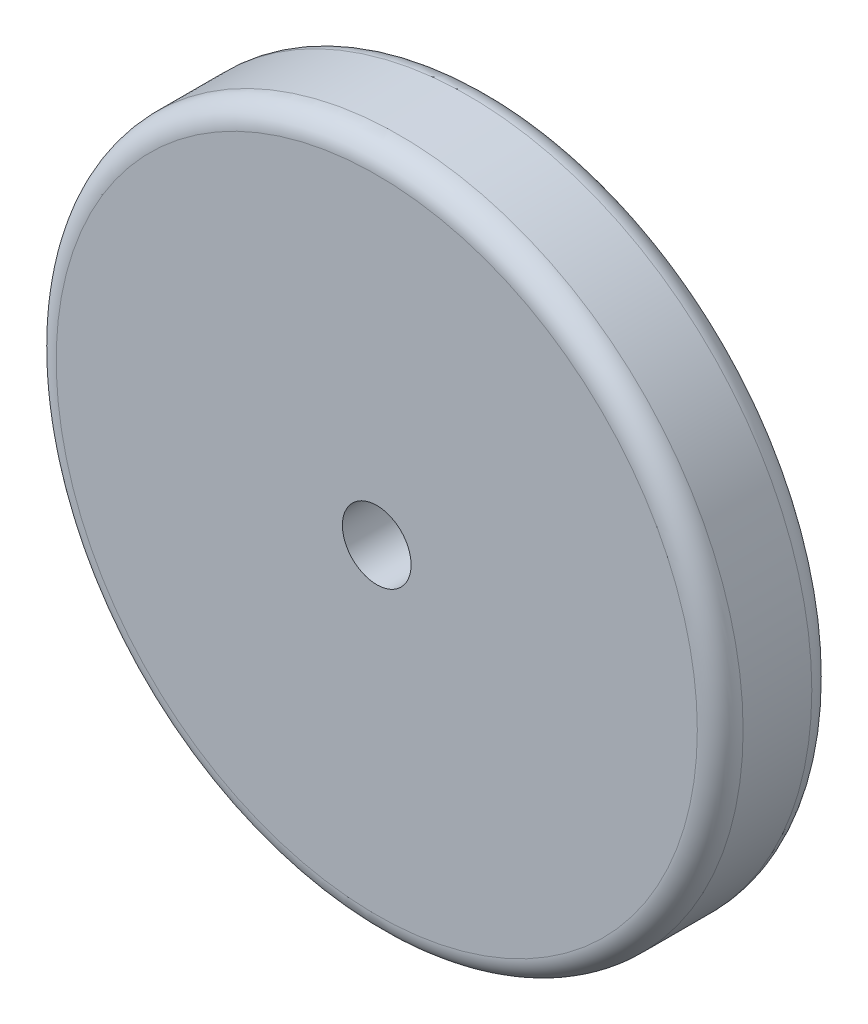
SolidWorks part; units mm, degrees
ref_plane "Alzado" through (0, 0, 0) normal (0, 0, 1) x (1, 0, 0)
ref_plane "Planta" through (0, 0, 0) normal (0, 1, 0) x (1, 0, 0)
ref_plane "Vista lateral" through (0, 0, 0) normal (1, 0, 0) x (0, 0, -1)
sketch "Croquis1" plane through (0, 0, 0) normal (0, 0, 1) x (1, 0, 0)
  circle A0 centre (0, 0) radius 7.5
extrude "Saliente-Extruir1" add sketch "Croquis1" along normal blind 2.5
sketch "Croquis2" plane through (0, 0, 0) normal (0, 0, -1) x (-1, 0, 0)
  circle A1 centre (0, 0) radius 0.75
extrude "Cortar-Extruir1" cut sketch "Croquis2" against normal blind 2.5
fillet "Redondeo1" radius 0.5 2 edges at (7.5, 0, 2.5) (7.5, 0, 0)
